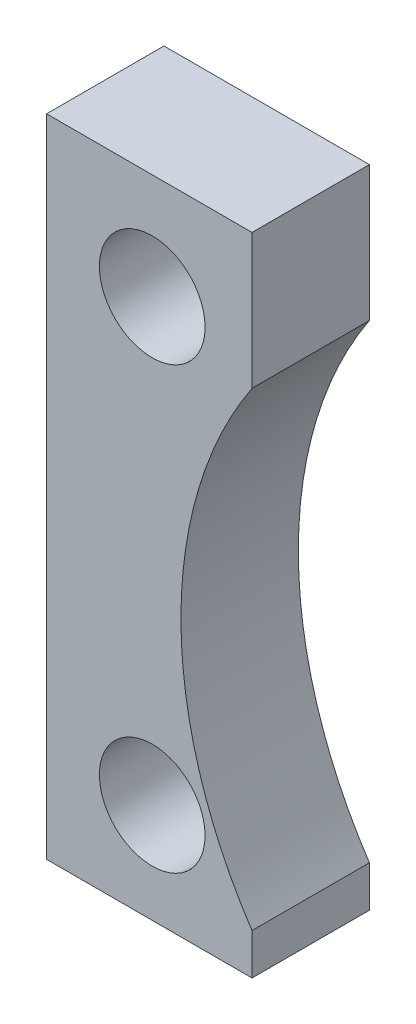
SolidWorks part; units mm, degrees
ref_plane "Ön Düzlem" through (0, 0, 0) normal (0, 0, 1) x (1, 0, 0)
ref_plane "Üst Düzlem" through (0, 0, 0) normal (0, 1, 0) x (1, 0, 0)
ref_plane "Sağ Düzlem" through (0, 0, 0) normal (1, 0, 0) x (0, 0, -1)
sketch "Sketch1" plane through (0, 0, 0) normal (0, 0, 1) x (1, 0, 0)
  line L0 (0, 110) -> (35, 110)
  line L1 (0, 110) -> (0, 0)
  line L2 (0, 0) -> (35, 0)
  line L3 (35, 110) -> (35, 87)
  line L4 (35, 7) -> (35, 0)
  arc A0 (35, 87) -> (35, 7) centre (95, 47) ccw
  dimension "D1" = 110
  dimension "D2" = 35
  dimension "D3" = 7
  dimension "D4" = 23
  dimension "D5" = 95
extrude "Boss-Extrude1" add sketch "Sketch1" along normal mid plane 20
sketch "Sketch2" plane through (0, 0, 10) normal (0, 0, 1) x (1, 0, 0)
  line L0 (0, 110) -> (0, 0) construction
  circle A0 centre (18, 92) radius 9
  circle A1 centre (18, 17) radius 9
  dimension "D3" = 18
  dimension "D1" = 75
  dimension "D2" = 18
extrude "Cut-Extrude1" cut sketch "Sketch2" against normal through all
